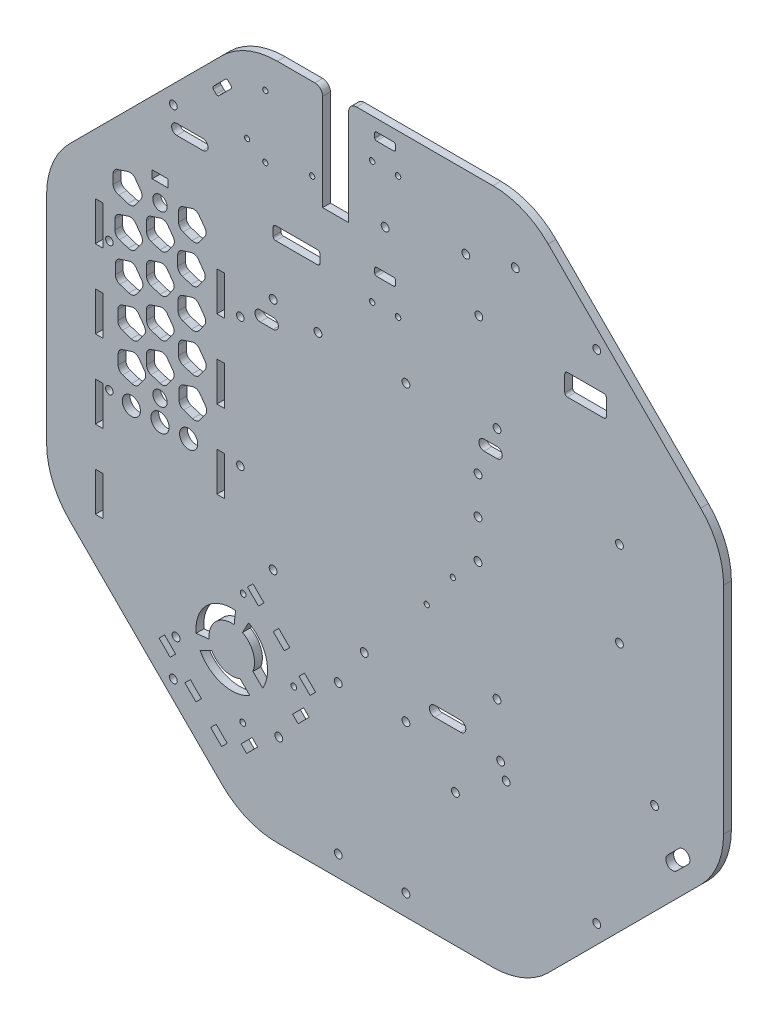
SolidWorks part; units mm, degrees
ref_plane "Front Plane" through (0, 0, 0) normal (0, 0, 1) x (1, 0, 0)
ref_plane "Top Plane" through (0, 0, 0) normal (0, 1, 0) x (1, 0, 0)
ref_plane "Right Plane" through (0, 0, 0) normal (1, 0, 0) x (0, 0, -1)
sketch "Sketch1" plane through (0, 0, 0) normal (0, 0, 1) x (1, 0, 0)
  line L0 (-179.569, 0) -> (179.66, 0) construction
  line L9 (0, 178.9146) -> (0, -184.198) construction
  line L10 (130, 17.5) -> (130, 41.4214)
  line L15 (121.2132, 62.6346) -> (62.6346, 121.2132)
  line L16 (41.4214, 130) -> (-41.4214, 130)
  line L17 (-62.6346, 121.2132) -> (-121.2132, 62.6346)
  line L24 (-130, 41.4214) -> (-130, 17.5)
  line L25 (-121.2132, -62.6346) -> (-62.6346, -121.2132)
  line L26 (-41.4214, -130) -> (41.4214, -130)
  line L27 (62.6346, -121.2132) -> (121.2132, -62.6346)
  line L28 (130, -41.4214) -> (130, -17.5)
  line L36 (-130, -17.5) -> (-130, -41.4214)
  line L37 (130, 17.5) -> (130, -17.5)
  line L38 (-130, 17.5) -> (-130, -17.5)
  arc A0 (128.8167, 17.5) -> (-128.8167, 17.5) centre (0, 0) ccw construction
  arc A1 (41.4214, -130) -> (62.6346, -121.2132) centre (41.4214, -100) ccw
  arc A2 (-62.6346, -121.2132) -> (-41.4214, -130) centre (-41.4214, -100) ccw
  arc A3 (121.2132, -62.6346) -> (130, -41.4214) centre (100, -41.4214) ccw
  arc A4 (121.2132, 62.6346) -> (130, 41.4214) centre (100, 41.4214) cw
  arc A5 (-130, -41.4214) -> (-121.2132, -62.6346) centre (-100, -41.4214) ccw
  arc A6 (62.6346, 121.2132) -> (41.4214, 130) centre (41.4214, 100) ccw
  arc A7 (-41.4214, 130) -> (-62.6346, 121.2132) centre (-41.4214, 100) ccw
  arc A8 (-121.2132, 62.6346) -> (-130, 41.4214) centre (-100, 41.4214) ccw
  arc A9 (-128.8167, -17.5) -> (128.8167, -17.5) centre (0, 0) ccw construction
  dimension "D2" = 30
  dimension "D1" = 260
extrude "Boss-Extrude1" add sketch "Sketch1" along normal blind 3
sketch "Sketch2" plane through (0, 0, 0) normal (0, 0, 1) x (1, 0, 0)
  line L0 (-193.4567, 0) -> (175.9011, 0) construction
  line L5 (-144.5676, 144.5676) -> (127.1387, -127.1387) construction
  line L30 (437.9113, 323.7635) -> (652.4254, 323.7635) construction
  line L39 (-111.2814, 64.3479) -> (-61.6325, 64.3479) construction
  line L40 (-62.6346, 121.2132) -> (-121.2132, 62.6346) construction
  line L48 (62.6346, -121.2132) -> (121.2132, -62.6346) construction
  line L54 (0, 165.2491) -> (0, -188.9622) construction
  line L55 (-40, 82.3245) -> (-40, 13.1803) construction
  line L56 (-64.6325, 34.3479) -> (-61.6325, 34.3479)
  line L57 (-67.579, -75.347) -> (-72.5516, -75.8696)
  line L58 (-66.6027, -78.5402) -> (-71.0174, -80.8876)
  line L59 (-57.4461, -60.757) -> (-57.9687, -65.7296)
  line L60 (-50.7422, -77.6556) -> (-47.0137, -81.3841)
  line L61 (-52.4217, -62.2918) -> (-54.769, -66.7065)
  line L62 (-55.6537, -82.567) -> (-51.9252, -86.2955)
  line L63 (-53.2151, -106.1765) -> (-55.3364, -104.0551)
  line L64 (-55.3364, -104.0551) -> (-51.0938, -99.8125)
  line L65 (-48.9724, -101.9338) -> (-51.0938, -99.8125)
  line L66 (-53.2151, -106.1765) -> (-48.9724, -101.9338)
  line L67 (-31.2948, -80.0135) -> (-35.5374, -84.2561)
  line L68 (-33.4161, -86.3775) -> (-35.5374, -84.2561)
  line L69 (-29.1735, -82.1348) -> (-33.4161, -86.3775)
  line L70 (-29.1735, -82.1348) -> (-31.2948, -80.0135)
  line L71 (-62.761, -108.6513) -> (-60.6397, -106.53)
  line L72 (-62.761, -108.6513) -> (-67.0037, -104.4087)
  line L73 (-67.0037, -104.4087) -> (-64.8824, -102.2874)
  line L74 (-60.6397, -106.53) -> (-64.8824, -102.2874)
  line L75 (-72.6605, -98.7518) -> (-76.9032, -94.5092)
  line L76 (-76.9032, -94.5092) -> (-74.7818, -92.3879)
  line L77 (-70.5392, -96.6305) -> (-74.7818, -92.3879)
  line L78 (-72.6605, -98.7518) -> (-70.5392, -96.6305)
  line L79 (-82.56, -88.8523) -> (-86.8027, -84.6097)
  line L80 (-86.8027, -84.6097) -> (-84.6813, -82.4884)
  line L81 (-80.4387, -86.731) -> (-84.6813, -82.4884)
  line L82 (-82.56, -88.8523) -> (-80.4387, -86.731)
  line L83 (-40.8407, -58.4) -> (-42.962, -60.5214)
  line L84 (-38.7194, -64.764) -> (-42.962, -60.5214)
  line L85 (-36.5981, -62.6427) -> (-38.7194, -64.764)
  line L86 (-36.5981, -62.6427) -> (-40.8407, -58.4)
  line L87 (-50.7402, -48.5005) -> (-52.8615, -50.6219)
  line L88 (-48.6189, -54.8645) -> (-52.8615, -50.6219)
  line L89 (-46.4976, -52.7432) -> (-48.6189, -54.8645)
  line L90 (-30.9412, -68.2995) -> (-33.0625, -70.4209)
  line L91 (-28.8199, -74.6635) -> (-33.0625, -70.4209)
  line L92 (-26.6986, -72.5422) -> (-28.8199, -74.6635)
  line L93 (-26.6986, -72.5422) -> (-30.9412, -68.2995)
  line L94 (-46.4976, -52.7432) -> (-50.7402, -48.5005)
  line L96 (-60.382, -117.5514) -> (-111.2814, -66.6521) construction
  line L98 (-17.7392, -75.0454) -> (-61.6325, -31.1521) construction
  line L99 (-61.6325, -31.1521) -> (-61.6325, 73.9968) construction
  line L100 (-61.6325, 73.9968) -> (-101.6325, 73.9968) construction
  line L101 (-101.6325, 73.9968) -> (-111.2814, 64.3479) construction
  line L102 (-111.2814, 64.3479) -> (-111.2814, -66.6521) construction
  line L103 (-121.2132, -62.6346) -> (-62.6346, -121.2132) construction
  line L104 (-130, 41.4214) -> (-130, -41.4214) construction
  line L105 (-89.4569, 69.8479) -> (-83.4569, 69.8479)
  line L106 (-89.4569, 69.8479) -> (-89.4569, 66.8479)
  line L107 (-89.4569, 66.8479) -> (-83.4569, 66.8479)
  line L108 (-83.4569, 69.8479) -> (-83.4569, 66.8479)
  line L109 (-108.2814, 49.3479) -> (-111.2814, 49.3479)
  line L110 (-108.2814, 49.3479) -> (-108.2814, 34.3479)
  line L111 (-108.2814, 34.3479) -> (-111.2814, 34.3479)
  line L112 (-111.2814, 49.3479) -> (-111.2814, 34.3479)
  line L113 (-108.2814, 19.3479) -> (-111.2814, 19.3479)
  line L114 (-108.2814, 19.3479) -> (-108.2814, 4.3479)
  line L115 (-108.2814, 4.3479) -> (-111.2814, 4.3479)
  line L116 (-111.2814, 19.3479) -> (-111.2814, 4.3479)
  line L117 (-108.2814, -10.6521) -> (-111.2814, -10.6521)
  line L118 (-108.2814, -10.6521) -> (-108.2814, -25.6521)
  line L119 (-108.2814, -25.6521) -> (-111.2814, -25.6521)
  line L120 (-111.2814, -10.6521) -> (-111.2814, -25.6521)
  line L121 (-108.2814, -40.6521) -> (-111.2814, -40.6521)
  line L122 (-108.2814, -40.6521) -> (-108.2814, -55.6521)
  line L123 (-108.2814, -55.6521) -> (-111.2814, -55.6521)
  line L124 (-111.2814, -40.6521) -> (-111.2814, -55.6521)
  line L125 (-86.4569, 64.3479) -> (-86.4569, -53.641) construction
  line L126 (-86.4569, 64.3479) -> (-86.4569, 73.9968) construction
  line L127 (-61.6325, 49.3479) -> (-61.6325, 34.3479)
  line L128 (-64.6325, 49.3479) -> (-64.6325, 34.3479)
  line L129 (-64.6325, 49.3479) -> (-61.6325, 49.3479)
  line L130 (-64.6325, 19.3479) -> (-61.6325, 19.3479)
  line L131 (-61.6325, 19.3479) -> (-61.6325, 4.3479)
  line L132 (-64.6325, 19.3479) -> (-64.6325, 4.3479)
  line L133 (-64.6325, 4.3479) -> (-61.6325, 4.3479)
  line L134 (-64.6325, -10.6521) -> (-61.6325, -10.6521)
  line L135 (-64.6325, -10.6521) -> (-64.6325, -25.6521)
  line L136 (-64.6325, -25.6521) -> (-61.6325, -25.6521)
  line L137 (-61.6325, -10.6521) -> (-61.6325, -25.6521)
  line L169 (-93.8388, 60.7508) -> (-95.9741, 63.6897)
  line L170 (-104.4637, 61.0977) -> (-104.4637, 57.465)
  line L171 (-95.9863, 54.8729) -> (-93.851, 57.8119)
  line L172 (-98.7692, 64.5979) -> (-102.2241, 63.4753)
  line L173 (-102.2363, 55.0873) -> (-98.7814, 53.9648)
  line L174 (-93.6686, 45.9677) -> (-95.8039, 48.9066)
  line L175 (-103.7814, 46.3146) -> (-103.7814, 42.6818)
  line L176 (-95.8039, 40.0898) -> (-93.6686, 43.0287)
  line L177 (-98.599, 49.8148) -> (-102.0539, 48.6922)
  line L178 (-102.0539, 40.3042) -> (-98.599, 39.1816)
  line L179 (-93.4863, 31.1845) -> (-95.6215, 34.1235)
  line L180 (-103.599, 31.5314) -> (-103.599, 27.8987)
  line L181 (-95.6215, 25.3067) -> (-93.4863, 28.2456)
  line L182 (-98.4166, 35.0316) -> (-101.8715, 33.9091)
  line L183 (-101.8715, 25.5211) -> (-98.4166, 24.3985)
  line L184 (-92.5314, 16.4014) -> (-94.6666, 19.3403)
  line L185 (-102.6441, 16.7483) -> (-102.6441, 13.1156)
  line L186 (-94.6666, 10.5235) -> (-92.5314, 13.4625)
  line L187 (-97.4617, 20.2485) -> (-100.9166, 19.1259)
  line L188 (-100.9166, 10.7379) -> (-97.4617, 9.6154)
  line L189 (-92.4054, 1.6202) -> (-94.5406, 4.5591)
  line L190 (-102.5181, 1.9671) -> (-102.5181, -1.6656)
  line L191 (-94.5406, -4.2577) -> (-92.4054, -1.3188)
  line L192 (-97.3357, 5.4673) -> (-100.7906, 4.3447)
  line L193 (-100.7906, -4.0433) -> (-97.3357, -5.1659)
  line L194 (-69.3067, 60.7508) -> (-71.442, 63.6897)
  line L195 (-79.3148, 61.0977) -> (-79.3148, 57.465)
  line L196 (-71.3374, 54.8729) -> (-69.2021, 57.8119)
  line L197 (-74.2371, 64.5979) -> (-77.692, 63.4753)
  line L198 (-77.5874, 55.0873) -> (-74.1325, 53.9648)
  line L199 (-69.5645, 45.9677) -> (-71.6998, 48.9066)
  line L200 (-79.6772, 46.3146) -> (-79.6772, 42.6818)
  line L201 (-71.6998, 40.0898) -> (-69.5645, 43.0287)
  line L202 (-74.4949, 49.8148) -> (-77.9498, 48.6922)
  line L203 (-77.9498, 40.3042) -> (-74.4949, 39.1816)
  line L204 (-69.3821, 31.1845) -> (-71.5174, 34.1235)
  line L205 (-79.4949, 31.5314) -> (-79.4949, 27.8987)
  line L206 (-71.5174, 25.3067) -> (-69.3821, 28.2456)
  line L207 (-74.3125, 35.0316) -> (-77.7674, 33.9091)
  line L208 (-77.7674, 25.5211) -> (-74.3125, 24.3985)
  line L209 (-69.1998, 16.4014) -> (-71.335, 19.3403)
  line L210 (-79.3125, 16.7483) -> (-79.3125, 13.1156)
  line L211 (-71.335, 10.5235) -> (-69.1998, 13.4625)
  line L212 (-74.1301, 20.2485) -> (-77.585, 19.1259)
  line L213 (-77.585, 10.7379) -> (-74.1301, 9.6154)
  line L214 (-69.0174, 1.6183) -> (-71.1527, 4.5572)
  line L215 (-79.1301, 1.9652) -> (-79.1301, -1.6676)
  line L216 (-71.1527, -4.2596) -> (-69.0174, -1.3207)
  line L217 (-73.9477, 5.4654) -> (-77.4027, 4.3428)
  line L218 (-77.4027, -4.0452) -> (-73.9477, -5.1678)
  line L219 (-81.3442, 51.5008) -> (-83.4794, 54.4397)
  line L220 (-91.6393, 51.8477) -> (-91.6393, 48.215)
  line L221 (-83.6618, 45.6229) -> (-81.5266, 48.5619)
  line L222 (-86.2745, 55.3479) -> (-89.7294, 54.2253)
  line L223 (-89.9118, 45.8373) -> (-86.4569, 44.7148)
  line L224 (-81.5266, 36.7177) -> (-83.6618, 39.6566)
  line L225 (-91.6393, 37.0646) -> (-91.6393, 33.4318)
  line L226 (-83.6618, 30.8398) -> (-81.5266, 33.7787)
  line L227 (-86.4569, 40.5648) -> (-89.9118, 39.4422)
  line L228 (-89.9118, 31.0542) -> (-86.4569, 29.9316)
  line L229 (-81.5266, 21.9345) -> (-83.6618, 24.8735)
  line L230 (-91.6393, 22.2814) -> (-91.6393, 18.6487)
  line L231 (-83.6618, 16.0567) -> (-81.5266, 18.9956)
  line L232 (-86.4569, 25.7816) -> (-89.9118, 24.6591)
  line L233 (-89.9118, 16.2711) -> (-86.4569, 15.1485)
  line L234 (-81.5266, 7.1514) -> (-83.6618, 10.0903)
  line L235 (-91.6393, 7.4983) -> (-91.6393, 3.8656)
  line L236 (-83.6618, 1.2735) -> (-81.5266, 4.2125)
  line L237 (-86.4569, 10.9985) -> (-89.9118, 9.8759)
  line L238 (-89.9118, 1.4879) -> (-86.4569, 0.3654)
  line L239 (-111.2814, -66.6521) -> (-61.6325, -31.1521) construction
  line L240 (-111.2814, -66.6521) -> (-91.6393, -66.6521) construction
  line L241 (-86.8027, -84.6097) -> (-111.2814, -60.131) construction
  line L242 (-61.6325, -31.1521) -> (-61.6325, -41.8494) construction
  line L243 (-50.7402, -48.5005) -> (-61.6325, -37.6083) construction
  line L244 (-53.9823, -45.2584) -> (-90.0681, -81.3442) construction
  line L245 (41.4214, 130) -> (-41.4214, 130) construction
  line L246 (-8.4795, 91.55) -> (7.9234, 91.55) construction
  line L247 (-24.5782, 130) -> (-24.5782, 132) construction
  line L248 (-14, 132) -> (-24, 132)
  line L249 (-14, 132) -> (-14, 90)
  line L250 (-14, 90) -> (-24, 90)
  line L251 (-24, 132) -> (-24, 90)
  line L252 (-24.5782, 132) -> (-24.2942, 132) construction
  line L253 (-103.599, -12.6521) -> (-70.259, -12.6521) construction
  arc A16 (-54.769, -66.7065) -> (-50.7422, -77.6556) centre (-58.8769, -74.4323) cw
  arc A17 (-52.4217, -62.2918) -> (-47.0137, -81.3841) centre (-58.8769, -74.4323) cw
  arc A18 (-67.579, -75.347) -> (-57.9687, -65.7296) centre (-58.8769, -74.4323) cw
  arc A19 (-72.5516, -75.8696) -> (-57.4461, -60.757) centre (-58.8769, -74.4323) cw
  arc A20 (-51.9252, -86.2955) -> (-71.0174, -80.8876) centre (-58.8769, -74.4323) cw
  arc A21 (-55.6537, -82.567) -> (-66.6027, -78.5402) centre (-58.8769, -74.4323) cw
  circle A22 centre (-80.2973, -80.9327) radius 1.1
  circle A23 centre (-54.6627, -96.6678) radius 1.1
  circle A24 centre (-54.5212, -53.6758) radius 1.1
  circle A25 centre (-35.0758, -74.8183) radius 1.1
  circle A26 centre (-40.8407, -94.5092) radius 1.5
  arc A58 (-104.4637, 57.465) -> (-102.2363, 55.0873) centre (-101.966, 57.5727) ccw
  arc A59 (-98.7814, 53.9648) -> (-95.9863, 54.8729) centre (-98.0088, 56.3424) ccw
  arc A60 (-102.2241, 63.4753) -> (-104.4637, 61.0977) centre (-101.9661, 60.9887) ccw
  arc A61 (-95.9741, 63.6897) -> (-98.7692, 64.5979) centre (-97.9966, 62.2203) ccw
  arc A62 (-93.8388, 60.7508) -> (-93.851, 57.8119) centre (-95.8674, 59.2897) cw
  arc A63 (-103.7814, 42.6818) -> (-102.0539, 40.3042) centre (-101.2814, 42.6818) ccw
  arc A64 (-98.599, 39.1816) -> (-95.8039, 40.0898) centre (-97.8264, 41.5593) ccw
  arc A65 (-102.0539, 48.6922) -> (-103.7814, 46.3146) centre (-101.2814, 46.3146) ccw
  arc A66 (-95.8039, 48.9066) -> (-98.599, 49.8148) centre (-97.8264, 47.4371) ccw
  arc A67 (-93.6686, 45.9677) -> (-93.6686, 43.0287) centre (-95.6912, 44.4982) cw
  arc A68 (-103.599, 27.8987) -> (-101.8715, 25.5211) centre (-101.099, 27.8987) ccw
  arc A69 (-98.4166, 24.3985) -> (-95.6215, 25.3067) centre (-97.6441, 26.7761) ccw
  arc A70 (-101.8715, 33.9091) -> (-103.599, 31.5314) centre (-101.099, 31.5314) ccw
  arc A71 (-95.6215, 34.1235) -> (-98.4166, 35.0316) centre (-97.6441, 32.654) ccw
  arc A72 (-93.4863, 31.1845) -> (-93.4863, 28.2456) centre (-95.5088, 29.7151) cw
  arc A73 (-102.6441, 13.1156) -> (-100.9166, 10.7379) centre (-100.1441, 13.1156) ccw
  arc A74 (-97.4617, 9.6154) -> (-94.6666, 10.5235) centre (-96.6891, 11.993) ccw
  arc A75 (-100.9166, 19.1259) -> (-102.6441, 16.7483) centre (-100.1441, 16.7483) ccw
  arc A76 (-94.6666, 19.3403) -> (-97.4617, 20.2485) centre (-96.6891, 17.8709) ccw
  arc A77 (-92.5314, 16.4014) -> (-92.5314, 13.4625) centre (-94.5539, 14.9319) cw
  arc A78 (-102.5181, -1.6656) -> (-100.7906, -4.0433) centre (-100.0181, -1.6656) ccw
  arc A79 (-97.3357, -5.1659) -> (-94.5406, -4.2577) centre (-96.5632, -2.7882) ccw
  arc A80 (-100.7906, 4.3447) -> (-102.5181, 1.9671) centre (-100.0181, 1.9671) ccw
  arc A81 (-94.5406, 4.5591) -> (-97.3357, 5.4673) centre (-96.5632, 3.0896) ccw
  arc A82 (-92.4054, 1.6202) -> (-92.4054, -1.3188) centre (-94.4279, 0.1507) cw
  arc A83 (-79.3148, 57.465) -> (-77.5874, 55.0873) centre (-76.8148, 57.465) ccw
  arc A84 (-74.1325, 53.9648) -> (-71.3374, 54.8729) centre (-73.3599, 56.3424) ccw
  arc A85 (-77.692, 63.4753) -> (-79.3148, 61.0977) centre (-76.8151, 61.1342) ccw
  arc A86 (-71.442, 63.6897) -> (-74.2371, 64.5979) centre (-73.4645, 62.2203) ccw
  arc A87 (-69.3067, 60.7508) -> (-69.2021, 57.8119) centre (-71.275, 59.2094) cw
  arc A88 (-79.6772, 42.6818) -> (-77.9498, 40.3042) centre (-77.1772, 42.6818) ccw
  arc A89 (-74.4949, 39.1816) -> (-71.6998, 40.0898) centre (-73.7223, 41.5593) ccw
  arc A90 (-77.9498, 48.6922) -> (-79.6772, 46.3146) centre (-77.1772, 46.3146) ccw
  arc A91 (-71.6998, 48.9066) -> (-74.4949, 49.8148) centre (-73.7223, 47.4371) ccw
  arc A92 (-69.5645, 45.9677) -> (-69.5645, 43.0287) centre (-71.5871, 44.4982) cw
  arc A93 (-79.4949, 27.8987) -> (-77.7674, 25.5211) centre (-76.9949, 27.8987) ccw
  arc A94 (-74.3125, 24.3985) -> (-71.5174, 25.3067) centre (-73.5399, 26.7761) ccw
  arc A95 (-77.7674, 33.9091) -> (-79.4949, 31.5314) centre (-76.9949, 31.5314) ccw
  arc A96 (-71.5174, 34.1235) -> (-74.3125, 35.0316) centre (-73.5399, 32.654) ccw
  arc A97 (-69.3821, 31.1845) -> (-69.3821, 28.2456) centre (-71.4047, 29.7151) cw
  arc A98 (-79.3125, 13.1156) -> (-77.585, 10.7379) centre (-76.8125, 13.1156) ccw
  arc A99 (-74.1301, 9.6154) -> (-71.335, 10.5235) centre (-73.3576, 11.993) ccw
  arc A100 (-77.585, 19.1259) -> (-79.3125, 16.7483) centre (-76.8125, 16.7483) ccw
  arc A101 (-71.335, 19.3403) -> (-74.1301, 20.2485) centre (-73.3576, 17.8709) ccw
  arc A102 (-69.1998, 16.4014) -> (-69.1998, 13.4625) centre (-71.2223, 14.9319) cw
  arc A103 (-79.1301, -1.6676) -> (-77.4027, -4.0452) centre (-76.6301, -1.6676) ccw
  arc A104 (-73.9477, -5.1678) -> (-71.1527, -4.2596) centre (-73.1752, -2.7901) ccw
  arc A105 (-77.4027, 4.3428) -> (-79.1301, 1.9652) centre (-76.6301, 1.9652) ccw
  arc A106 (-71.1527, 4.5572) -> (-73.9477, 5.4654) centre (-73.1752, 3.0877) ccw
  arc A107 (-69.0174, 1.6183) -> (-69.0174, -1.3207) centre (-71.0399, 0.1488) cw
  arc A108 (-91.6393, 48.215) -> (-89.9118, 45.8373) centre (-89.1393, 48.215) ccw
  arc A109 (-86.4569, 44.7148) -> (-83.6618, 45.6229) centre (-85.6844, 47.0924) ccw
  arc A110 (-89.7294, 54.2253) -> (-91.6393, 51.8477) centre (-89.1398, 51.7959) ccw
  arc A111 (-83.4794, 54.4397) -> (-86.2745, 55.3479) centre (-85.502, 52.9703) ccw
  arc A112 (-81.3442, 51.5008) -> (-81.5266, 48.5619) centre (-83.452, 50.1565) cw
  arc A113 (-91.6393, 33.4318) -> (-89.9118, 31.0542) centre (-89.1393, 33.4318) ccw
  arc A114 (-86.4569, 29.9316) -> (-83.6618, 30.8398) centre (-85.6844, 32.3093) ccw
  arc A115 (-89.9118, 39.4422) -> (-91.6393, 37.0646) centre (-89.1393, 37.0646) ccw
  arc A116 (-83.6618, 39.6566) -> (-86.4569, 40.5648) centre (-85.6844, 38.1871) ccw
  arc A117 (-81.5266, 36.7177) -> (-81.5266, 33.7787) centre (-83.5491, 35.2482) cw
  arc A118 (-91.6393, 18.6487) -> (-89.9118, 16.2711) centre (-89.1393, 18.6487) ccw
  arc A119 (-86.4569, 15.1485) -> (-83.6618, 16.0567) centre (-85.6844, 17.5261) ccw
  arc A120 (-89.9118, 24.6591) -> (-91.6393, 22.2814) centre (-89.1393, 22.2814) ccw
  arc A121 (-83.6618, 24.8735) -> (-86.4569, 25.7816) centre (-85.6844, 23.404) ccw
  arc A122 (-81.5266, 21.9345) -> (-81.5266, 18.9956) centre (-83.5491, 20.4651) cw
  arc A123 (-91.6393, 3.8656) -> (-89.9118, 1.4879) centre (-89.1393, 3.8656) ccw
  arc A124 (-86.4569, 0.3654) -> (-83.6618, 1.2735) centre (-85.6844, 2.743) ccw
  arc A125 (-89.9118, 9.8759) -> (-91.6393, 7.4983) centre (-89.1393, 7.4983) ccw
  arc A126 (-83.6618, 10.0903) -> (-86.4569, 10.9985) centre (-85.6844, 8.6209) ccw
  arc A127 (-81.5266, 7.1514) -> (-81.5266, 4.2125) centre (-83.5491, 5.6819) cw
  circle A128 centre (-86.4569, -4.6346) radius 2.75
  circle A129 centre (-86.4569, 60.3479) radius 2.75
  circle A130 centre (4.98, 115) radius 1.05
  circle A131 centre (-4.98, 115) radius 1.05
  circle A132 centre (-4.98, 68.1) radius 1.05
  circle A133 centre (4.98, 68.1) radius 1.05
  circle A134 centre (-97.4569, -12.6521) radius 3.5
  circle A135 centre (-75.4569, -12.6521) radius 3.5
  circle A136 centre (-86.4569, -12.6521) radius 3.5
  point P40 (-86.4569, 66.8479)
  point P42 (-86.4569, 69.8479)
  point P59 (-91.9239, 91.9239)
  point P62 (91.9239, -91.9239)
  point P189 (-46.9771, -80.0667)
  dimension "D36" = 2.5
  dimension "D38" = 5.5
  dimension "D39" = 4
  dimension "D40" = 5
  dimension "D41" = 0.5
  dimension "D42" = 0.5
  dimension "D43" = 5
  dimension "D44" = 12.5
  dimension "D45" = 12.5
  dimension "D46" = 180
  dimension "D47" = 15.404
  dimension "D48" = 30
  dimension "D49" = 4.6181
  dimension "D50" = 3
  dimension "D51" = 2.1
  dimension "D52" = 15
  dimension "D53" = 5.5
  dimension "D58" = 4.15
  dimension "D65" = 4.98
  dimension "D66" = 23.45
  dimension "D67" = 42
  dimension "D71" = 7
  dimension "D72" = 11
  dimension "D74" = 7
  dimension "D75" = 7
  dimension "D2" = 131
  dimension "D3" = 6
  dimension "D4" = 3
  dimension "D5" = 8
  dimension "D6" = 8
  dimension "D7" = 22
  dimension "D8" = 8.7932
  dimension "D9" = 8.7932
  dimension "D10" = 8.7932
  dimension "D11" = 45
  dimension "D12" = 17.2932
  dimension "D13" = 6
  dimension "D14" = 4.5652
  dimension "D15" = 4.5652
  dimension "D16" = 4.5652
  dimension "D17" = 7.5652
  dimension "D18" = 7.5652
  dimension "D19" = 7.5652
  dimension "D20" = 90
  dimension "D21" = 3
  dimension "D22" = 15
  dimension "10" = 15
  dimension "D23" = 6
  dimension "D24" = 3
  dimension "D25" = 0
  dimension "D26" = 49.6489
  dimension "D27" = 40
  dimension "D28" = 15
  dimension "D29" = 15
  dimension "D30" = 15
  dimension "D31" = 4.1821
  dimension "D32" = 18.7186
  dimension "D33" = 15
  dimension "D34" = 15
  dimension "D35" = 15
  dimension "D37" = 5.5
  dimension "D54" = 4.15
  dimension "D55" = 4.15
  dimension "D56" = 4.15
  dimension "D57" = 4.15
  dimension "D59" = 4.15
  dimension "D60" = 4.15
  dimension "D61" = 4.15
  dimension "D62" = 4.15
  dimension "D63" = 4.15
  dimension "D64" = 4.15
  dimension "D68" = 10
  dimension "D69" = 14
  dimension "D70" = 2
  dimension "D73" = 11
  dimension "D76" = 77
extrude "Cut-Extrude2" cut sketch "Sketch2" along normal blind 10
fillet "Fillet1" radius 3 2 edges at (-14, 130, 1.5) (-24, 130, 1.5)
sketch "Sketch4" plane through (0, 0, 3) normal (0, 0, 1) x (1, 0, 0)
  line L0 (12.4086, 0) -> (-180.4379, 0) construction
  line L1 (-105.9, 37.94) -> (-55.6, 37.94) construction
  line L2 (-105.9, -11.7) -> (-55.6, -11.7) construction
  line L3 (-105.9, 37.94) -> (-105.9, -11.7) construction
  line L4 (-55.6, 37.94) -> (-55.6, -11.7) construction
  line L6 (123.6331, 618.6076) -> (1115.6331, 618.6076) construction
  line L7 (130, -41.4214) -> (130, 41.4214) construction
  line L8 (85, 82.2) -> (69, 82.2)
  line L9 (85, 82.2) -> (85, 74)
  line L10 (85, 74) -> (69, 74)
  line L11 (69, 82.2) -> (69, 74)
  line L12 (-41.4214, -130) -> (41.4214, -130) construction
  line L13 (41.4214, 130) -> (-11, 130) construction
  line L16 (-27, 130) -> (-41.4214, 130) construction
  line L17 (-130, 41.4214) -> (-130, -41.4214) construction
  line L18 (-25, 75) -> (-43, 75)
  line L19 (-25, 75) -> (-25, 70)
  line L20 (-25, 70) -> (-43, 70)
  line L21 (-43, 75) -> (-43, 70)
  circle A0 centre (-105.9, 37.94) radius 1.45
  circle A1 centre (-55.6, 37.94) radius 1.45
  circle A2 centre (-105.9, -11.7) radius 1.45
  circle A3 centre (-55.6, -11.7) radius 1.45
  circle A4 centre (44.3687, -59.9526) radius 1.5
  circle A5 centre (103.4987, -45.1026) radius 1.5
  dimension "D1" = 2.9
  dimension "D3" = 2.9
  dimension "D8" = 3
  dimension "D9" = 3
  dimension "D2" = 50.3
  dimension "D4" = 50.3
  dimension "D5" = 49.64
  dimension "D6" = 5
  dimension "D7" = 24.1
  dimension "D10" = 26.5013
  dimension "D11" = 84.8974
  dimension "D12" = 59.13
  dimension "D13" = 14.85
  dimension "D14" = 8.2
  dimension "D15" = 16
  dimension "D16" = 45
  dimension "D17" = 56
  dimension "D18" = 11.7
  dimension "D19" = 18
  dimension "D20" = 87
  dimension "D21" = 55
extrude "Cut-Extrude3" cut sketch "Sketch4" against normal blind 10
fillet "Fillet2" radius 1 4 edges at (-25, 70, 1.5) (-43, 75, 1.5) (-43, 70, 1.5) (-25, 75, 1.5)
sketch "Sketch5" plane through (0, 0, 3) normal (0, 0, 1) x (1, 0, 0)
  line L0 (90, 35) -> (90, 2.13) construction
  line L1 (120, 50) -> (60, 50) construction
  line L2 (120, 50) -> (120, -39) construction
  line L3 (120, -39) -> (60, -39) construction
  line L4 (60, 50) -> (60, -39) construction
  line L5 (130, -41.4214) -> (130, 41.4214) construction
  line L6 (41.4214, 130) -> (-11, 130) construction
  line L7 (-18, -65) -> (-18, -122) construction
  line L8 (-18, -122) -> (8, -122) construction
  line L9 (8, -122) -> (8, -65) construction
  line L10 (8, -65) -> (-18, -65) construction
  line L11 (-41.4214, -130) -> (41.4214, -130) construction
  line L12 (-130, 41.4214) -> (-130, -41.4214) construction
  line L14 (19, -56) -> (29, -56) construction
  line L15 (19, -54) -> (29, -54)
  line L16 (19, -58) -> (29, -58)
  line L17 (-80, 88) -> (-70, 88) construction
  line L18 (-80, 90) -> (-70, 90)
  line L19 (-80, 86) -> (-70, 86)
  line L20 (-27, 130) -> (-41.4214, 130) construction
  line L21 (-44.3083, 47.5915) -> (35.694, 47.5915) construction
  line L22 (35.694, 47.5915) -> (35.694, -9.7856) construction
  circle A0 centre (90, 35) radius 1.5
  circle A1 centre (90, 2.13) radius 1.5
  circle A2 centre (-18, -65) radius 1.5
  circle A4 centre (8, -122) radius 1.5
  circle A5 centre (-18, -122) radius 1.5
  circle A6 centre (8, -65) radius 1.5
  circle A7 centre (46.5, -65.5) radius 1.5
  circle A8 centre (27, -79) radius 1.5
  circle A9 centre (-8, -50) radius 1.5
  circle A10 centre (-80.2973, -80.9327) radius 1.5
  arc A11 (19, -54) -> (19, -58) centre (19, -56) ccw
  arc A12 (29, -58) -> (29, -54) centre (29, -56) ccw
  circle A13 centre (8, 47.5915) radius 1.5
  circle A14 centre (-25.7769, 47.5915) radius 1.5
  circle A15 centre (35.694, 31.2699) radius 1.5
  circle A16 centre (35.694, 16.9928) radius 1.5
  circle A17 centre (35.694, 2.13) radius 1.5
  arc A18 (-80, 90) -> (-80, 86) centre (-80, 88) ccw
  arc A19 (-70, 86) -> (-70, 90) centre (-70, 88) ccw
  point P28 (24, -56)
  point P52 (-75, 88)
  dimension "D3" = 3
  dimension "D4" = 3
  dimension "D6" = 30
  dimension "D12" = 3
  dimension "D13" = 8
  dimension "D15" = 3
  dimension "D18" = 3
  dimension "D21" = 3
  dimension "D24" = 3
  dimension "D25" = 2
  dimension "D30" = 2
  dimension "D33" = 3
  dimension "D1" = 89
  dimension "D2" = 60
  dimension "D5" = 32.87
  dimension "D7" = 15
  dimension "D8" = 10
  dimension "D9" = 80
  dimension "D10" = 57
  dimension "D11" = 26
  dimension "D14" = 112
  dimension "D16" = 64.5
  dimension "D17" = 83.5
  dimension "D19" = 51
  dimension "D20" = 19.5
  dimension "D22" = 15
  dimension "D23" = 68
  dimension "D26" = 10
  dimension "D27" = 16
  dimension "D28" = 9
  dimension "D29" = 10
  dimension "D31" = 55
  dimension "D32" = 42
extrude "Cut-Extrude4" cut sketch "Sketch5" against normal blind 10
sketch "Sketch6" plane through (0, 0, 3) normal (0, 0, 1) x (1, 0, 0)
  line L0 (-43, 50) -> (-43, -39.078) construction
  line L1 (-130, 41.4214) -> (-130, -41.4214) construction
  line L2 (-27, 130) -> (-41.4214, 130) construction
  line L3 (43, 50) -> (43, -42.3574) construction
  line L4 (130, -41.4214) -> (130, 41.4214) construction
  line L5 (41.4214, 130) -> (-11, 130) construction
  line L6 (0, 139.6282) -> (0, -148.6682) construction
  line L7 (-159.8415, 0) -> (173.7215, 0) construction
  line L8 (91.9239, -91.9239) -> (87.9151, -87.9151) construction
  line L9 (-91.9239, -91.9239) -> (-89.8633, -89.8633) construction
  line L10 (-121.2132, -62.6346) -> (-62.6346, -121.2132) construction
  line L11 (62.6346, -121.2132) -> (121.2132, -62.6346) construction
  line L12 (91.9239, 91.9239) -> (87.9151, 87.9151) construction
  line L13 (121.2132, 62.6346) -> (62.6346, 121.2132) construction
  line L14 (-91.9239, 91.9239) -> (-88.7271, 88.7271) construction
  line L15 (-62.6346, 121.2132) -> (-121.2132, 62.6346) construction
  line L16 (-14, 127) -> (-14, 90) construction
  line L17 (-58.6899, 112.43) -> (-64.3467, 106.7731)
  line L18 (69, 74) -> (85, 74) construction
  line L19 (-43, 42) -> (-48, 42) construction
  line L20 (-43, 40) -> (-48, 40)
  line L21 (-43, 44) -> (-48, 44)
  line L22 (43, 42) -> (38, 42) construction
  line L23 (43, 40) -> (38, 40)
  line L24 (43, 44) -> (38, 44)
  line L25 (-14, 90) -> (-24, 90) construction
  line L26 (-28, 98.5) -> (-55.4937, 98.5) construction
  line L27 (-58.6899, 112.43) -> (-60.8112, 114.5513)
  line L28 (-64.3467, 106.7731) -> (-66.468, 108.8944)
  line L29 (-60.8112, 114.5513) -> (-66.468, 108.8944)
  line L30 (-24, 90) -> (-24, 127) construction
  line L31 (-46, 123.0828) -> (-46, 91.5216) construction
  line L32 (114.5513, -56.5685) -> (110.3087, -60.8112) construction
  line L33 (-17.1274, 101.5) -> (17.6027, 101.5) construction
  line L34 (-4, 122.5) -> (4, 122.5)
  line L35 (-4, 122.5) -> (-4, 125.5)
  line L36 (-4, 125.5) -> (4, 125.5)
  line L37 (4, 122.5) -> (4, 125.5)
  line L38 (-4, 122.5) -> (4, 125.5) construction
  line L39 (-4, 125.5) -> (4, 122.5) construction
  line L40 (-4, 77.5) -> (4, 77.5)
  line L41 (4, 80.5) -> (4, 77.5)
  line L42 (-4, 80.5) -> (4, 80.5)
  line L43 (-4, 80.5) -> (-4, 77.5)
  line L44 (116.3191, -58.3363) -> (112.0764, -62.579)
  line L45 (112.7835, -54.8008) -> (108.5409, -59.0434)
  circle A0 centre (-43, -40) radius 1.5
  circle A1 centre (-43, 50) radius 1.5
  circle A2 centre (43, -40) radius 1.5
  circle A3 centre (43, 50) radius 1.5
  circle A5 centre (-81.3173, -95.4594) radius 1.5
  circle A6 centre (81.3173, -95.4594) radius 1.5
  circle A7 centre (81.3173, 95.4594) radius 1.5
  circle A8 centre (-81.3173, 95.4594) radius 1.5
  circle A9 centre (16, -22) radius 1
  circle A10 centre (26, -8) radius 1
  circle A11 centre (31, 102) radius 1.5
  circle A12 centre (50, 107) radius 1.5
  circle A13 centre (36, 84) radius 1.5
  arc A14 (-43, 40) -> (-43, 44) centre (-43, 42) ccw
  arc A15 (-48, 44) -> (-48, 40) centre (-48, 42) ccw
  arc A16 (43, 40) -> (43, 44) centre (43, 42) ccw
  arc A17 (38, 44) -> (38, 40) centre (38, 42) ccw
  circle A18 centre (-28, 98.5) radius 1
  circle A19 centre (-53, 98.5) radius 1
  circle A20 centre (-46, 118) radius 1
  circle A21 centre (-46, 94) radius 1
  circle A22 centre (0, 95.5) radius 1.5
  arc A23 (116.3191, -58.3363) -> (112.7835, -54.8008) centre (114.5513, -56.5685) ccw
  arc A24 (108.5409, -59.0434) -> (112.0764, -62.579) centre (110.3087, -60.8112) ccw
  point P57 (-45.5, 42)
  point P69 (40.5, 42)
  point P79 (-19, 90)
  point P98 (0, 124)
  point P110 (112.43, -58.6899)
  point P115 (110.8243, -60.7896)
  dimension "D1" = 3
  dimension "D8" = 3
  dimension "D19" = 2
  dimension "D29" = 2
  dimension "D33" = 2
  dimension "D47" = 15
  dimension "D48" = 2.5
  dimension "D2" = 87
  dimension "D3" = 90
  dimension "D4" = 80
  dimension "D5" = 87
  dimension "D6" = 90
  dimension "D7" = 80
  dimension "D9" = 5
  dimension "D10" = 10
  dimension "D11" = 10
  dimension "D12" = 5
  dimension "D13" = 10
  dimension "D14" = 5
  dimension "D15" = 10
  dimension "D16" = 5
  dimension "D17" = 14
  dimension "D18" = 10
  dimension "D20" = 27
  dimension "D21" = 18
  dimension "D22" = 19
  dimension "D23" = 5
  dimension "D24" = 18
  dimension "D25" = 5
  dimension "D26" = 45
  dimension "D27" = 10
  dimension "D28" = 5
  dimension "D30" = 8
  dimension "D31" = 8
  dimension "D32" = 9
  dimension "D34" = 8.5
  dimension "D35" = 25
  dimension "D36" = 8
  dimension "D37" = 3
  dimension "D38" = 6
  dimension "D39" = 30
  dimension "D40" = 24
  dimension "D41" = 22
  dimension "D42" = 12
  dimension "D43" = 8
  dimension "D44" = 3
  dimension "D45" = 6
  dimension "D46" = 28.5
  dimension "D49" = 6
  dimension "D50" = 9
  dimension "D51" = 35
extrude "Cut-Extrude5" cut sketch "Sketch6" against normal blind 10
fillet "Fillet3" radius 1 4 edges at (85, 82.2, 1.5) (69, 82.2, 1.5) (69, 74, 1.5) (85, 74, 1.5)
fillet "Fillet4" radius 0.7 12 edges at (4, 122.5, 1.5) (-4, 122.5, 1.5) (-4, 125.5, 1.5) (4, 125.5, 1.5) (-60.8112, 114.5513, 1.5) (-64.3467, 106.7731, 1.5) (-58.6899, 112.43, 1.5) (-66.468, 108.8944, 1.5) (4, 80.5, 1.5) (-4, 80.5, 1.5) (-4, 77.5, 1.5) (4, 77.5, 1.5)
